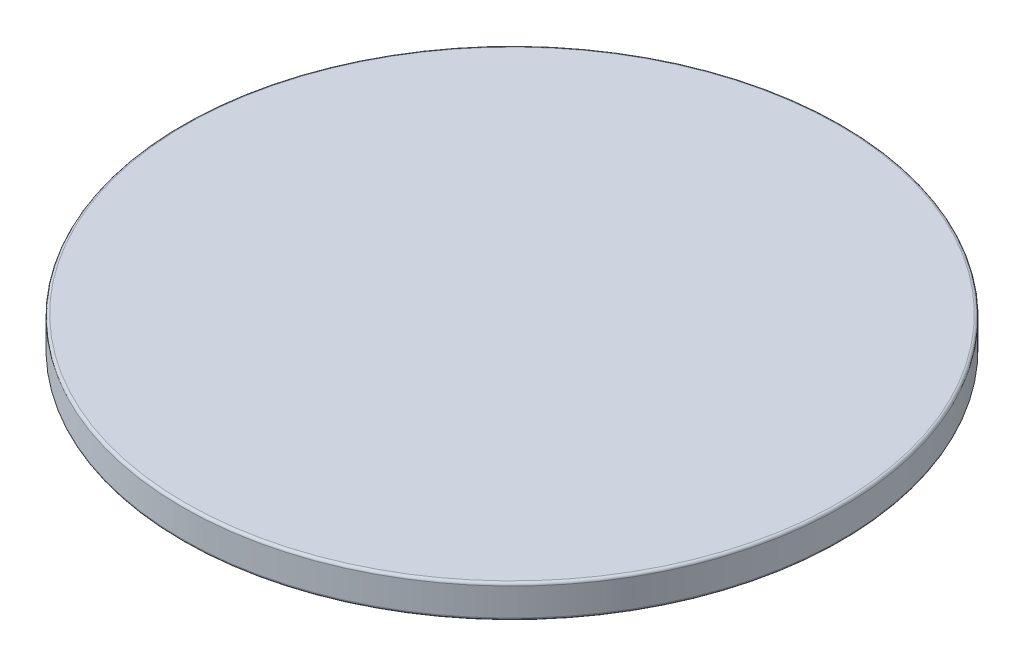
SolidWorks part; units mm, degrees
ref_plane "Front Plane" through (0, 0, 0) normal (0, 0, 1) x (1, 0, 0)
ref_plane "Top Plane" through (0, 0, 0) normal (0, 1, 0) x (1, 0, 0)
ref_plane "Right Plane" through (0, 0, 0) normal (1, 0, 0) x (0, 0, -1)
sketch "Sketch1" plane through (0, 0, 0) normal (0, 1, 0) x (1, 0, 0)
  line L0 (0, 0) -> (0, 250000) construction
  circle A0 centre (0, 0) radius 250000
  circle A1 centre (-42500, 195000) radius 25000 construction
  circle A2 centre (42500, 195000) radius 25000 construction
  circle A3 centre (190124.9537, -60693.9203) radius 25000 construction
  circle A4 centre (147624.9537, -134306.0797) radius 25000 construction
  circle A5 centre (-147624.9537, -134306.0797) radius 25000 construction
  circle A6 centre (-190124.9537, -60693.9203) radius 25000 construction
  point P18 (0, 0)
  dimension "D1" = 500000
  dimension "D4" = 50000
  dimension "D2" = 85000
  dimension "D3" = 195000
  dimension "D5" = 3
extrude "Boss-Extrude1" add sketch "Sketch1" against normal blind 25000
fillet "Fillet1" radius 2000 2 edges at (0, 0, 250000) (0, -25000, 250000)
